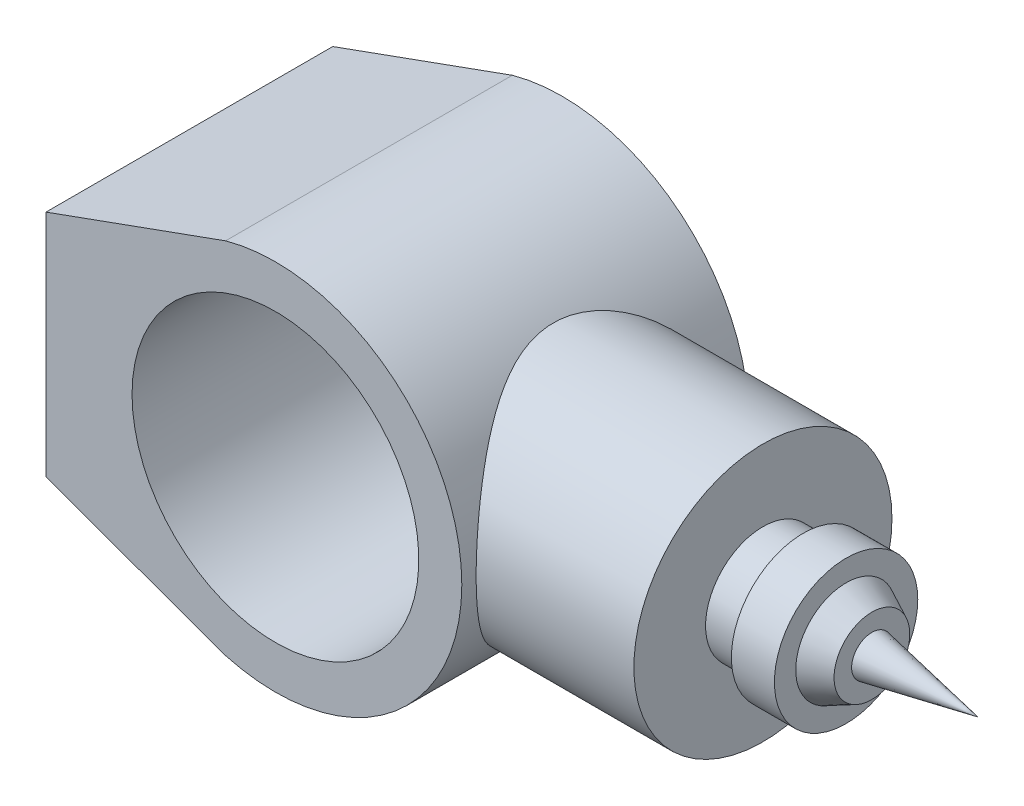
SolidWorks part; units mm, degrees
ref_plane "Front Plane" through (0, 0, 0) normal (0, 0, 1) x (1, 0, 0)
ref_plane "Top Plane" through (0, 0, 0) normal (0, 1, 0) x (1, 0, 0)
ref_plane "Right Plane" through (0, 0, 0) normal (1, 0, 0) x (0, 0, -1)
sketch "Sketch1" plane through (0, 0, 0) normal (0, 0, 1) x (1, 0, 0)
  line L0 (-80, -40) -> (-80, 40)
  line L1 (-80, 40) -> (-17.3681, 62.6367)
  line L2 (-80, -40) -> (-17.3681, -62.6367)
  arc A0 (-17.3681, -62.6367) -> (-17.3681, 62.6367) centre (0, 0) ccw
  circle A1 centre (0, 0) radius 50
  point P7 (-80, 0)
  dimension "D1" = 130
  dimension "D2" = 100
  dimension "D3" = 80
  dimension "D4" = 80
extrude "Boss-Extrude1" add sketch "Sketch1" along normal mid plane 100
ref_plane "Plane1" through (120, 0, 0) normal (1, 0, 0) x (0, 0, -1)
sketch "Sketch2" plane through (120, 0, 0) normal (1, 0, 0) x (0, 0, -1)
  circle A0 centre (0, 0) radius 45
  dimension "D1" = 90
extrude "Boss-Extrude2" add sketch "Sketch2" against normal up to next
sketch "Sketch3" plane through (0, 0, 0) normal (0, 0, 1) x (1, 0, 0)
  line L0 (353.9496, 0) -> (0, 0) construction
  line L1 (120, 0) -> (120, -20)
  line L2 (120, -45) -> (120, 45) construction
  line L3 (120, -20) -> (134, -20)
  line L4 (134, -20) -> (134, -25)
  line L5 (134, -25) -> (149, -25)
  line L11 (149, -25) -> (149, -17.5568)
  line L12 (149, -17.5568) -> (158, -13.1979)
  line L13 (158, -13.1979) -> (158, -7.0682)
  line L14 (158, -7.0682) -> (195, 0)
  line L15 (195, 0) -> (120, 0)
  dimension "D1" = 20
  dimension "D2" = 14
  dimension "D3" = 5
  dimension "D4" = 15
  dimension "D5" = 75
  dimension "D6" = 37
  dimension "D7" = 10
revolve "Revolve1" add sketch "Sketch3" angle 360 about L0
